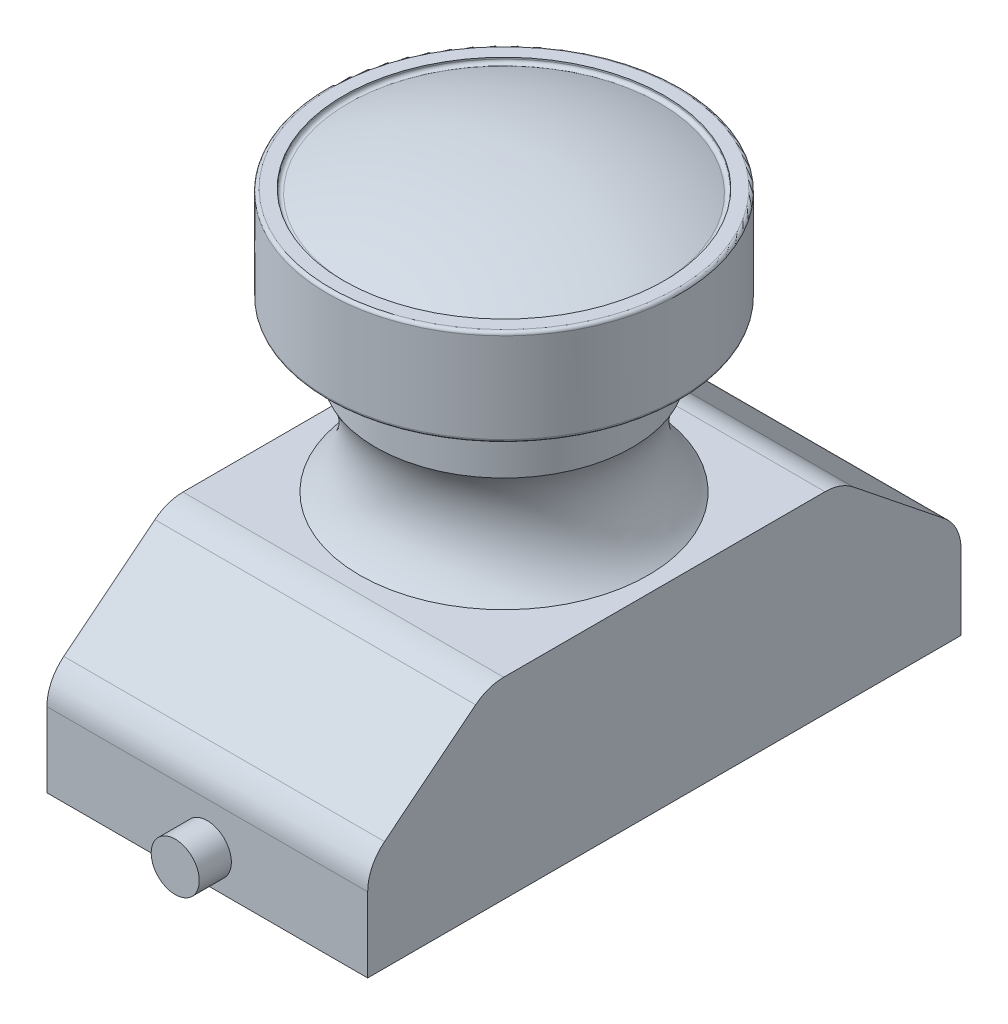
SolidWorks part; units mm, degrees
ref_plane "Front Plane" through (0, 0, 0) normal (0, 0, 1) x (1, 0, 0)
ref_plane "Top Plane" through (0, 0, 0) normal (0, 1, 0) x (1, 0, 0)
ref_plane "Right Plane" through (0, 0, 0) normal (1, 0, 0) x (0, 0, -1)
sketch "Sketch1" plane through (0, 0, 0) normal (1, 0, 0) x (0, 0, -1)
  line L0 (0, 6) -> (0, 0) construction
  line L1 (-9.25, 0) -> (9.25, 0)
  line L2 (9.25, 0) -> (9.25, 3)
  line L3 (9.25, 3) -> (5.5, 6)
  line L4 (5.5, 6) -> (-5.5, 6)
  line L5 (-9.25, 0) -> (-9.25, 3)
  line L6 (-9.25, 3) -> (-5.5, 6)
  point P5 (0, 0)
  dimension "D1" = 18.5
  dimension "D2" = 11
  dimension "D3" = 3
  dimension "D4" = 3
extrude "Boss-Extrude1" add sketch "Sketch1" along normal mid plane 10
sketch "Sketch2" plane through (0, 0, 0) normal (1, 0, 0) x (0, 0, -1)
  line L0 (0, 14) -> (0, 6)
  line L1 (0, 14) -> (5, 14)
  line L2 (5, 14) -> (5, 14.2)
  line L3 (5.5, 11.2) -> (4, 11.2)
  line L4 (4, 11.2) -> (4, 9.2)
  line L5 (5.5, 6) -> (-5.5, 6) construction
  line L6 (5, 14.2) -> (5.5, 14.2)
  line L7 (5.5, 14.2) -> (5.5, 11.2)
  line L8 (0, 6) -> (4.5, 6)
  arc A0 (4, 9.2) -> (4.5, 6) centre (6.1318, 7.894) ccw
  dimension "D5" = 2.5
  dimension "D1" = 8
  dimension "D2" = 4.5
  dimension "D3" = 5
  dimension "D4" = 2
  dimension "D6" = 0.5
  dimension "D7" = 0.2
  dimension "D8" = 3
  dimension "D9" = 1.5
revolve "Revolve1" add sketch "Sketch2" angle 360 about L0
sketch "Sketch3" plane through (0, 0, 0) normal (1, 0, 0) x (0, 0, -1)
  line L0 (0, 15) -> (0, 14.2)
  line L1 (5, 14.2) -> (-5, 14.2) construction
  line L2 (0, 14.2) -> (0, 14)
  line L3 (0, 14) -> (-5, 14)
  arc A0 (-5, 14) -> (0, 15) centre (-0.2003, 3.0017) cw
  dimension "D4" = 12
  dimension "D1" = 5
  dimension "D2" = 0.8
  dimension "D3" = 0.2
revolve "Revolve2" add sketch "Sketch3" angle 360 about L0
fillet "Fillet1" radius 0.1 3 edges at (0, 11.2, 5.5) (0, 14, 5) (0, 14.2, 5.5)
fillet "Fillet2" radius 1.4 4 edges at (0, 3, -9.25) (0, 3, 9.25) (0, 6, 5.5) (0, 6, -5.5)
sketch "Sketch4" plane through (0, 0, -9.25) normal (0, 0, -1) x (-1, 0, 0)
  circle A0 centre (0, 1) radius 0.75
  dimension "D1" = 1.5
  dimension "D2" = 1
extrude "Boss-Extrude2" add sketch "Sketch4" along normal mid plane 2
mirror "Mirror1" about plane through (0, 0, 0) normal (0, 0, 1) of "Boss-Extrude2"
